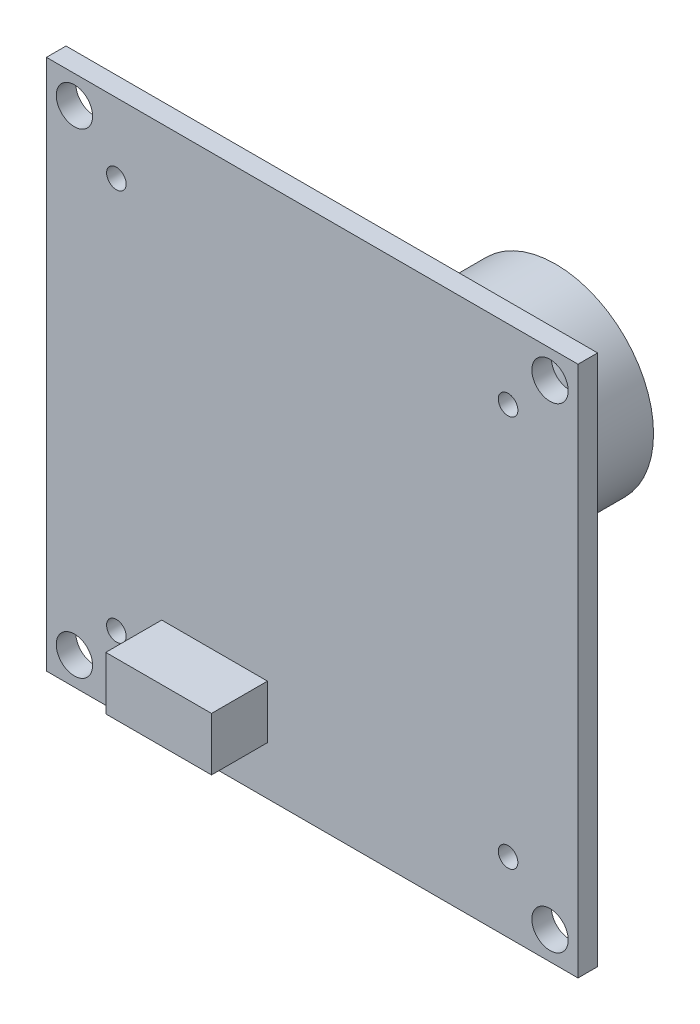
SolidWorks part; units mm, degrees
ref_plane "Front Plane" through (0, 0, 0) normal (0, 0, 1) x (1, 0, 0)
ref_plane "Top Plane" through (0, 0, 0) normal (0, 1, 0) x (1, 0, 0)
ref_plane "Right Plane" through (0, 0, 0) normal (1, 0, 0) x (0, 0, -1)
sketch "Sketch1" plane through (0, 0, 0) normal (0, 0, 1) x (1, 0, 0)
  line L0 (0.1, -1.3) -> (27.9, -1.3)
  line L1 (0, 0) -> (28, 0) construction
  line L2 (0, 0) -> (0, 28) construction
  line L3 (0, 28) -> (28, 28) construction
  line L4 (28, 0) -> (28, 28) construction
  line L5 (29.3, 0.1) -> (29.3, 27.9)
  line L6 (0.1, 29.3) -> (27.9, 29.3)
  line L7 (-1.3, 0.1) -> (-1.3, 27.9)
  line L8 (-1.3, -1.3) -> (29.3, -1.3) construction
  line L9 (-1.3, -1.3) -> (-1.3, 29.3) construction
  line L10 (29.3, -1.3) -> (29.3, 29.3) construction
  line L11 (-1.3, 29.3) -> (29.3, 29.3) construction
  line L12 (-5, 14) -> (14, 14) construction
  line L13 (-5, 33) -> (33, 33)
  line L14 (-5, 33) -> (-5, -5)
  line L15 (-5, -5) -> (33, -5)
  line L16 (33, 33) -> (33, -5)
  line L17 (14, 14) -> (33, 14) construction
  line L18 (14, 0) -> (14, 28) construction
  line L19 (-3, -3) -> (-3, 31) construction
  line L20 (-3, 31) -> (31, 31) construction
  line L21 (31, -3) -> (31, 31) construction
  line L22 (-3, -3) -> (31, -3) construction
  circle A0 centre (0, 28) radius 0.7
  circle A1 centre (28, 28) radius 0.7
  circle A2 centre (0, 0) radius 0.7
  circle A3 centre (28, 0) radius 0.7
  arc A4 (0.1, -1.3) -> (-1.3, 0.1) centre (0.1, 0.1) cw
  arc A5 (27.9, -1.3) -> (29.3, 0.1) centre (27.9, 0.1) ccw
  arc A6 (29.3, 27.9) -> (27.9, 29.3) centre (27.9, 27.9) ccw
  arc A7 (0.1, 29.3) -> (-1.3, 27.9) centre (0.1, 27.9) ccw
  circle A8 centre (-3, 31) radius 1.3
  circle A9 centre (31, 31) radius 1.3
  circle A10 centre (31, -3) radius 1.3
  circle A11 centre (-3, -3) radius 1.3
  dimension "D3" = 1.4
  dimension "D4" = 1.4
  dimension "D7" = 2.6
  dimension "D1" = 28
  dimension "D5" = 38
  dimension "D2" = 1.3
  dimension "D6" = 3
extrude "Boss-Extrude1" add sketch "Sketch1" along normal blind 1.4 contours L16 L13 L14 L15 A11 A10 A9 A8 A7 L6 A6 L5 A5 L0 A4 L7 | L6 A7 L7 A4 L0 A5 L5 A6 A0 A1 A2 A3
sketch "Sketch2" plane through (0, 0, 1.4) normal (0, 0, 1) x (1, 0, 0)
  line L1 (3.24, 2.28) -> (10.8, 2.28)
  line L2 (3.24, 2.28) -> (3.24, -1.53)
  line L3 (3.24, -1.53) -> (10.8, -1.53)
  line L4 (10.8, 2.28) -> (10.8, -1.53)
  line L6 (-5, 33) -> (-5, -5) construction
  line L7 (-5, -5) -> (33, -5) construction
  dimension "D1" = 8.24
  dimension "D2" = 3.47
  dimension "D3" = 3.81
  dimension "D4" = 7.56
extrude "Boss-Extrude2" add sketch "Sketch2" along normal blind 4 contours L1 L4 L3 L2
sketch "Sketch3" plane through (0, 0, 0) normal (0, 0, -1) x (-1, 0, 0)
  line L0 (-33, 14) -> (5, 14) construction
  line L3 (-33, 33) -> (-33, -5) construction
  line L4 (5, 33) -> (5, -5) construction
  circle A0 centre (-14, 14) radius 7
  dimension "D1" = 14
extrude "Boss-Extrude3" add sketch "Sketch3" along normal blind 16
